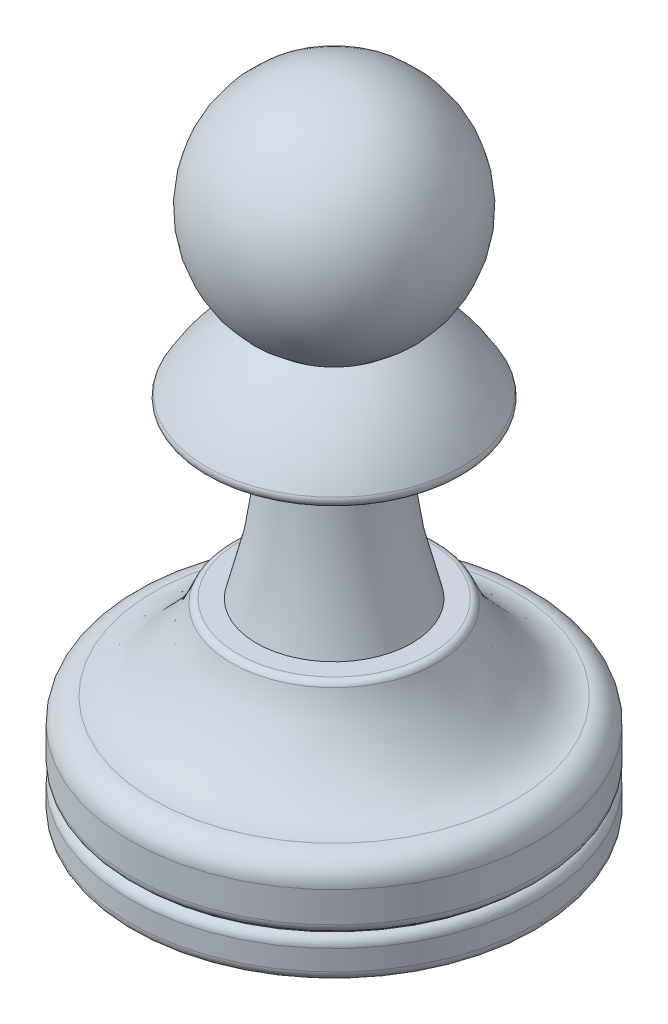
SolidWorks part; units mm, degrees
ref_plane "Front Plane" through (0, 0, 0) normal (0, 0, 1) x (1, 0, 0)
ref_plane "Top Plane" through (0, 0, 0) normal (0, 1, 0) x (1, 0, 0)
ref_plane "Right Plane" through (0, 0, 0) normal (1, 0, 0) x (0, 0, -1)
sketch "Sketch1" plane through (0, 0, 0) normal (0, 0, 1) x (1, 0, 0)
  line L0 (0, 0) -> (0, 95.25) construction
  dimension "D1" = 95.25
sketch "Sketch2" plane through (0, 0, 0) normal (0, 0, 1) x (1, 0, 0)
  line L0 (0, 0) -> (191.1891, 0) construction
  line L1 (185.5646, 4.755) -> (185.5646, 52.8583)
  line L2 (179.7527, 18.9488) -> (178.3606, 18.9488)
  line L3 (185.5646, 4.755) -> (171.0866, 4.755)
  line L4 (170.3246, 5.517) -> (170.3246, 7.041)
  line L5 (170.3246, 8.565) -> (170.3246, 10.851)
  line L6 (176.4424, 31.5092) -> (181.6199, 31.5092)
  line L7 (181.6199, 31.5092) -> (181.6199, 34.2611) construction
  line L8 (170.8832, 7.803) -> (185.5646, 7.803) construction
  line L9 (170.8326, 7.8466) -> (170.8326, 7.7594)
  arc A0 (185.5646, 52.8583) -> (180.7626, 37.3248) centre (185.5646, 44.3493) ccw
  arc A1 (181.6199, 31.5092) -> (179.7527, 18.9488) centre (138.4399, 31.5092) cw
  arc A2 (180.7626, 37.3248) -> (175.9975, 32.2624) centre (188.2326, 25.5197) ccw
  arc A3 (175.9975, 32.2624) -> (176.4424, 31.5092) centre (176.4424, 32.0172) ccw
  arc A4 (172.0606, 12.6285) -> (170.3246, 10.851) centre (172.1026, 10.851) ccw
  arc A5 (170.3246, 8.565) -> (170.8326, 7.8466) centre (171.0866, 8.565) ccw
  arc A6 (170.8326, 7.7594) -> (170.3246, 7.041) centre (171.0866, 7.041) ccw
  arc A7 (171.0866, 4.755) -> (170.3246, 5.517) centre (171.0866, 5.517) cw
  arc A8 (178.3606, 18.9488) -> (177.8782, 18.5999) centre (178.3606, 18.4408) ccw
  spline S0 degree 3 poles (177.8782, 18.5999) (177.416, 17.1987) (175.9025, 14.9312) (173.6246, 12.6655) (172.0606, 12.6285) knots 0.034687 0.034687 0.034687 0.034687 0.457601 0.915203 0.915203 0.915203 0.915203
  dimension "D2" = 17.018
  dimension "D3" = 0.508
  dimension "D4" = 1.778
  dimension "D5" = 0.762
  dimension "D6" = 0.762
  dimension "D7" = 0.508
  dimension "D9" = 43.18
  dimension "D10" = 13.97
  dimension "D13" = 15.24
  dimension "D8" = 48.1034
  dimension "D11" = 3.048
  dimension "D12" = 3.048
  dimension "D14" = 0.508
revolve "Pawn" add sketch "Sketch2" angle 360 about L1
